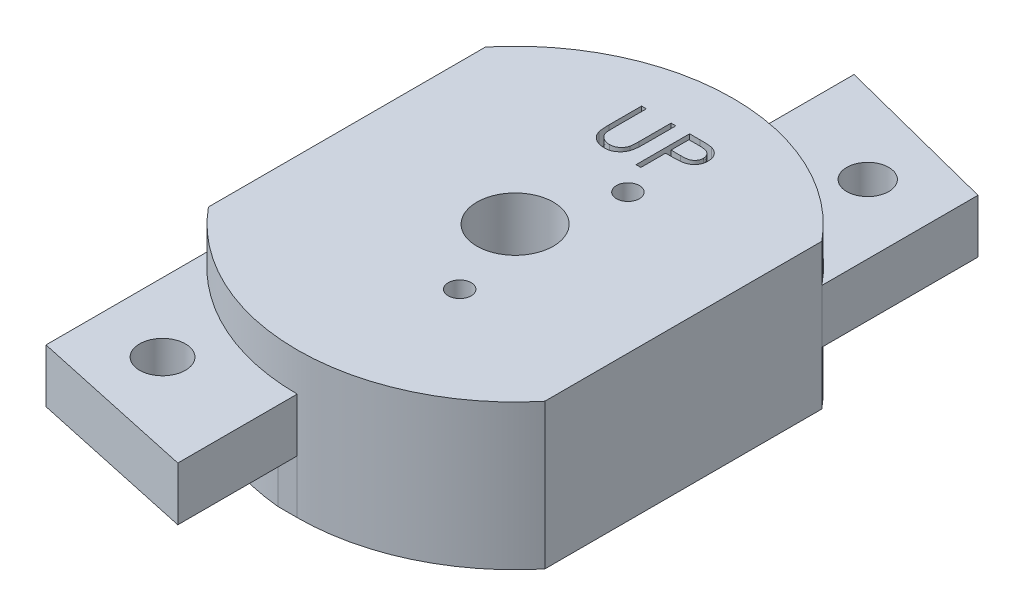
SolidWorks part; units mm, degrees
ref_plane "Front Plane" through (0, 0, 0) normal (0, 0, 1) x (1, 0, 0)
ref_plane "Top Plane" through (0, 0, 0) normal (0, 1, 0) x (1, 0, 0)
ref_plane "Right Plane" through (0, 0, 0) normal (1, 0, 0) x (0, 0, -1)
sketch "Sketch1" plane through (0, 0, 0) normal (0, 1, 0) x (1, 0, 0)
  line L2 (0, 5.1912) -> (0, 23.3088)
  line L4 (22, 5.1912) -> (22, 23.3088)
  line L5 (0, 0) -> (22, 28.5) construction
  line L6 (0, 28.5) -> (22, 0) construction
  arc A0 (22, 23.3088) -> (0, 23.3088) centre (11, 14.25) ccw
  arc A1 (0, 5.1912) -> (22, 5.1912) centre (11, 14.25) ccw
  circle A2 centre (11, 14.25) radius 2.5
  circle A3 centre (12.8754, 8.75) radius 0.75
  circle A4 centre (12.8754, 19.75) radius 0.75
  point P4 (11, 14.25)
  point P11 (11, 0)
  dimension "D5" = 5
  dimension "D6" = 1.5
  dimension "D7" = 1.5
  dimension "D1" = 22
  dimension "D2" = 28.5
  dimension "D3" = 5.1912
  dimension "D4" = 11
  dimension "D8" = 5.5
  dimension "D9" = 5.5
extrude "Boss-Extrude1" add sketch "Sketch1" along normal blind 6
sketch "Sketch2" plane through (0, 0, 0) normal (0, 1, 0) x (1, 0, 0)
  line L0 (11, -7.8088) -> (0, -5.4291)
  line L2 (0, 5.1912) -> (0, -5.4291)
  line L4 (11, 0) -> (11, -7.8088)
  line L5 (0, 5.1912) -> (11, -7.8088) construction
  line L6 (0, -7.8088) -> (11, 5.1912) construction
  line L7 (22, 5.1912) -> (22, 23.3088) construction
  line L12 (11.1071, 36.3088) -> (22, 33.5192)
  line L14 (22, 23.3088) -> (22, 33.5192)
  line L16 (11.1071, 28.5262) -> (11.1071, 36.3088)
  line L17 (22, 23.3088) -> (11.1071, 36.3088) construction
  line L18 (22, 36.3088) -> (11.1071, 23.3088) construction
  circle A0 centre (4.5, -2.3088) radius 1.5
  arc A1 (0, 5.1528) -> (11, 0) centre (11.1071, 14.5462) ccw
  arc A4 (0, 5.1912) -> (22, 5.1912) centre (11, 14.25) ccw construction
  circle A5 centre (17.5, 30.8088) radius 1.3737
  arc A6 (22, 23.3088) -> (11.1071, 28.5262) centre (11.1071, 14.5462) ccw
  point P4 (5.5, -1.3088)
  point P23 (16.5535, 29.8088)
  dimension "D3" = 3
  dimension "D8" = 13
  dimension "D7" = 7.5
  dimension "D1" = 13
  dimension "D2" = 11
  dimension "D4" = 4.5
  dimension "D5" = 7.5
  dimension "D6" = 4.5
extrude "Boss-Extrude4" add sketch "Sketch2" along normal blind 3.5 contours A6 L14 L12 L16 A5 | A1 L2 L0 L4 A0
sketch "Sketch4" plane through (0, 6, 0) normal (0, 1, 0) x (1, 0, 0)
  text T0 "UP"
  point P1 (7.1851, 21.2162)
  point P2 (0, 0)
  point P3 (0, 0)
  point P4 (7.9979, 21.5714)
extrude "Cut-Extrude1" cut sketch "Sketch4" against normal blind 1
sketch "Sketch6" plane through (0, 0, 0) normal (0, -1, 0) x (1, 0, 0)
  line L1 (12.247, 0) -> (9.753, 0)
  line L2 (22, -5.1244) -> (22, -23.3088)
  line L3 (12.247, -28.4333) -> (9.753, -28.4333)
  line L4 (0, 0) -> (0, -23.3088)
  line L5 (22, 0) -> (2.2667, -25.5037) construction
  line L6 (22, -28.4333) -> (0, 0) construction
  arc A0 (22, -5.1244) -> (0, -5.1244) centre (11, -14.2166) ccw
  arc A1 (0, -23.3088) -> (22, -23.3088) centre (11, -14.2166) ccw
  point P4 (11, -14.2166)
  arc M5 (0, -5.1528) -> (1.8888, -3.2933) centre (11.1071, -14.5462) cw
  arc M6 (1.8888, -3.2933) -> (0, -5.1912) centre (11, -14.25) ccw
  line M7 (0, -5.1912) -> (0, -23.3088)
  line M9 (22, -23.3088) -> (22, -5.1912)
  arc M10 (22, -5.1912) -> (11, 0) centre (11, -14.25) ccw
  circle M15 centre (11, -14.25) radius 2.5
  circle M16 centre (12.8754, -8.75) radius 0.75
  circle M17 centre (12.8754, -19.75) radius 0.75
extrude "Boss-Extrude6" add sketch "Sketch6" along normal blind 3.5 contours L3 A1 L1 A0 L4 M9 M10 M5 M6 M7 M15 M17 M16
